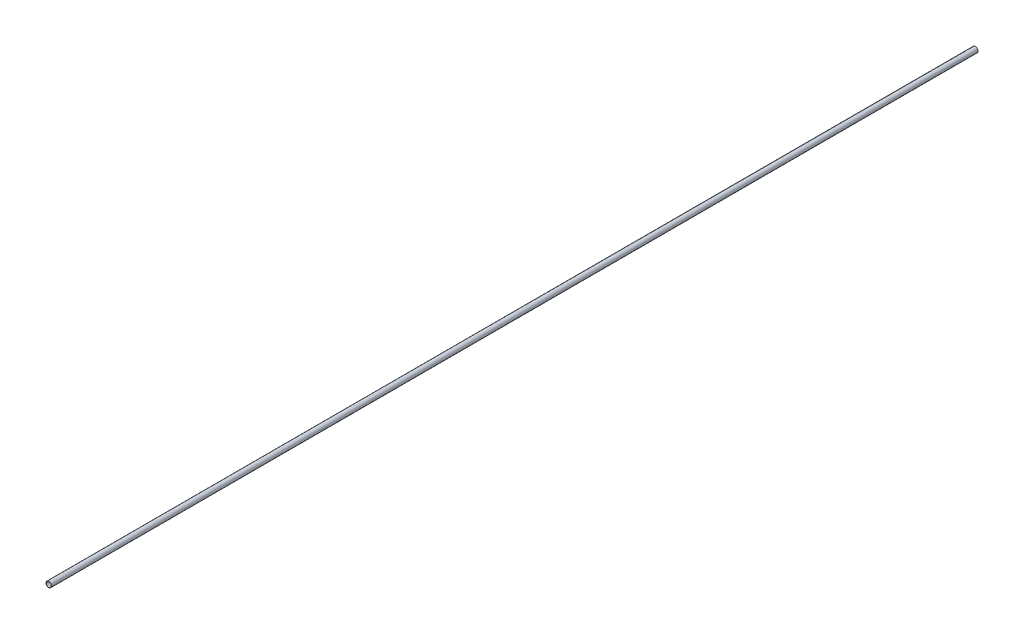
SolidWorks part; units mm, degrees
material "Galvanized Steel"
ref_plane "Front Plane" through (0, 0, 0) normal (0, 0, 1) x (1, 0, 0)
ref_plane "Top Plane" through (0, 0, 0) normal (0, 1, 0) x (1, 0, 0)
ref_plane "Right Plane" through (0, 0, 0) normal (1, 0, 0) x (0, 0, -1)
sketch "Sketch1" plane through (0, 0, 0) normal (0, 0, 1) x (1, 0, 0)
  circle A0 centre (0, 0) radius 7.8994
  circle A1 centre (0, 0) radius 8.9662
extrude "Boss-Extrude1" add sketch "Sketch1" along normal blind 3048
